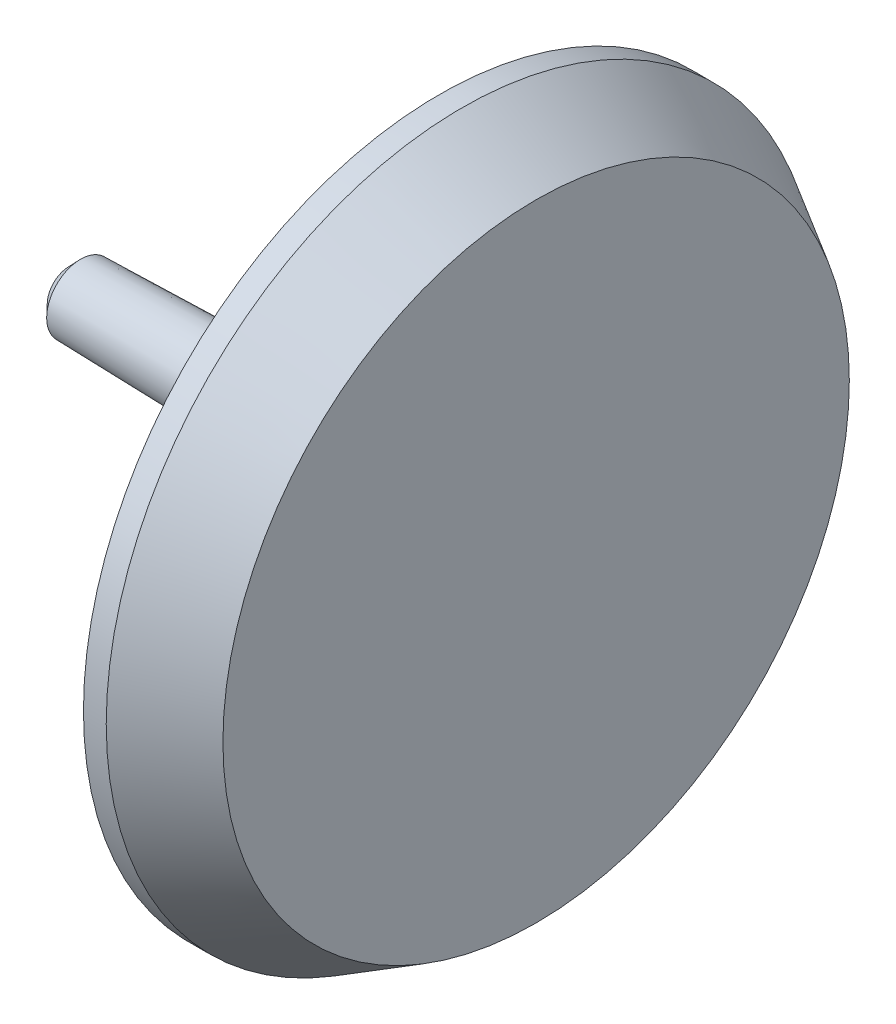
SolidWorks part; units mm, degrees
ref_plane "Front Plane" through (0, 0, 0) normal (0, 0, 1) x (1, 0, 0)
ref_plane "Top Plane" through (0, 0, 0) normal (0, 1, 0) x (1, 0, 0)
ref_plane "Right Plane" through (0, 0, 0) normal (1, 0, 0) x (0, 0, -1)
sketch "Sketch1" plane through (0, 0, 0) normal (0, 0, 1) x (1, 0, 0)
  line L0 (-13.7384, 0) -> (13.7384, 0) construction
  line L1 (0, 0) -> (0, 7.493)
  line L2 (0, 7.493) -> (66.04, 9.0805)
  line L3 (104.14, 0) -> (104.14, 69.85)
  line L4 (104.14, 69.85) -> (87.6422, 79.375)
  line L5 (87.6422, 79.375) -> (82.5622, 79.375)
  line L6 (82.5622, 79.375) -> (71.12, 9.0805)
  line L7 (71.12, 9.0805) -> (66.04, 9.0805)
  line L8 (0, 0) -> (104.14, 0)
  point P4 (0, 0)
  dimension "D1" = 14.986
  dimension "D2" = 18.161
  dimension "D3" = 66.04
  dimension "D4" = 139.7
  dimension "D5" = 158.75
  dimension "D6" = 30
  dimension "D7" = 38.1
  dimension "D8" = 5.08
revolve "Revolve1" add sketch "Sketch1" angle 360 about L0
fillet "Fillet1" radius 2.54 1 edges at (71.12, 0, 9.0805)
chamfer "Chamfer1" distance 2.54 angle 45 1 edges at (0, 0, 7.493)
